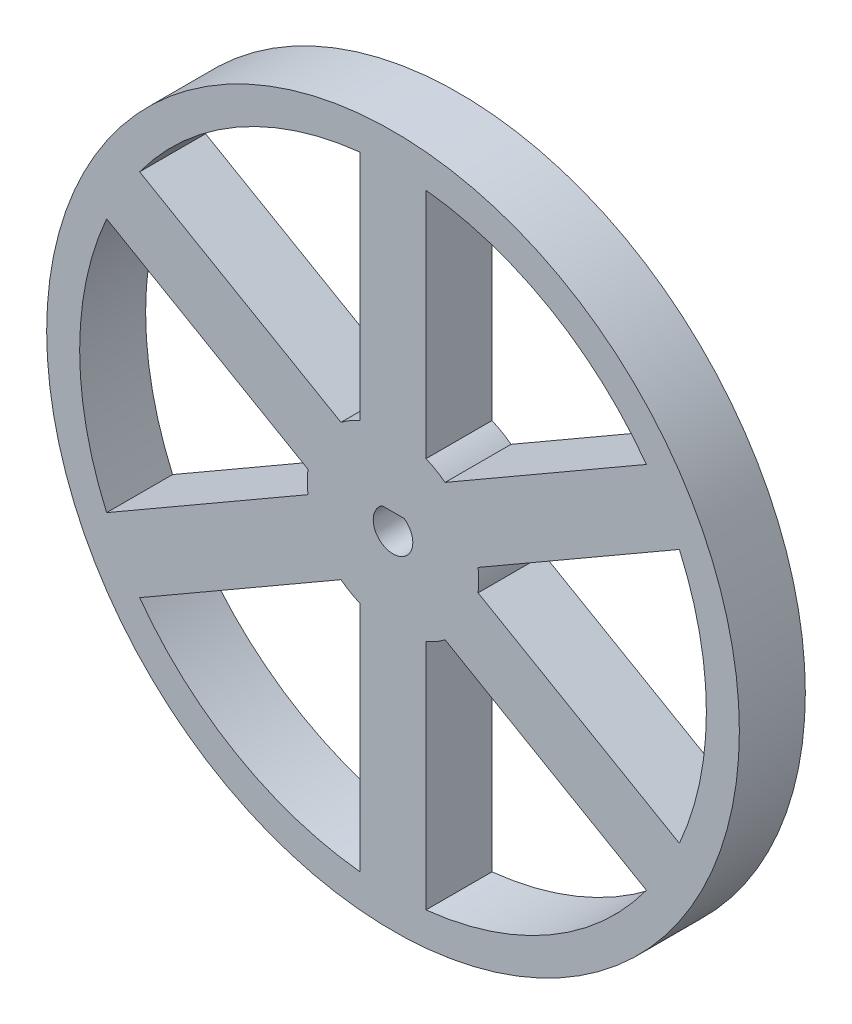
SolidWorks part; units mm, degrees
ref_plane "Front" through (0, 0, 0) normal (0, 0, 1) x (1, 0, 0)
ref_plane "Top" through (0, 0, 0) normal (0, 1, 0) x (1, 0, 0)
ref_plane "Right" through (0, 0, 0) normal (1, 0, 0) x (0, 0, -1)
sketch "Sketch1" plane through (0, 0, 0) normal (0, 0, 1) x (1, 0, 0)
  line L0 (-1.6583, 2.5) -> (1.6583, 2.5)
  line L1 (0, 0) -> (0, 57.7497) construction
  line L2 (-5, 47.2361) -> (-5, 12)
  line L3 (5, 47.2361) -> (5, 12)
  line L4 (43.4077, 19.2879) -> (12.8923, 1.6699)
  line L5 (38.4077, 27.9482) -> (7.8923, 10.3301)
  line L6 (38.4077, -27.9482) -> (7.8923, -10.3301)
  line L7 (43.4077, -19.2879) -> (12.8923, -1.6699)
  line L8 (-5, -47.2361) -> (-5, -12)
  line L9 (5, -47.2361) -> (5, -12)
  line L10 (-43.4077, -19.2879) -> (-12.8923, -1.6699)
  line L11 (-38.4077, -27.9482) -> (-7.8923, -10.3301)
  line L12 (-38.4077, 27.9482) -> (-7.8923, 10.3301)
  line L13 (-43.4077, 19.2879) -> (-12.8923, 1.6699)
  circle A0 centre (0, 0) radius 3
  circle A1 centre (0, 0) radius 47.5
  circle A2 centre (0, 0) radius 13
  circle A3 centre (0, 0) radius 52.5
  point P16 (7.253, 10.1806)
  point P17 (12.4073, 1.5194)
  point P37 (0, 0)
  dimension "D1" = 6
  dimension "D2" = 95
  dimension "D5" = 10
  dimension "D7" = 2.5
  dimension "D3" = 10
  dimension "D4" = 5
  dimension "D6" = 6
extrude "Boss-Extrude1" add sketch "Sketch1" along normal blind 10
